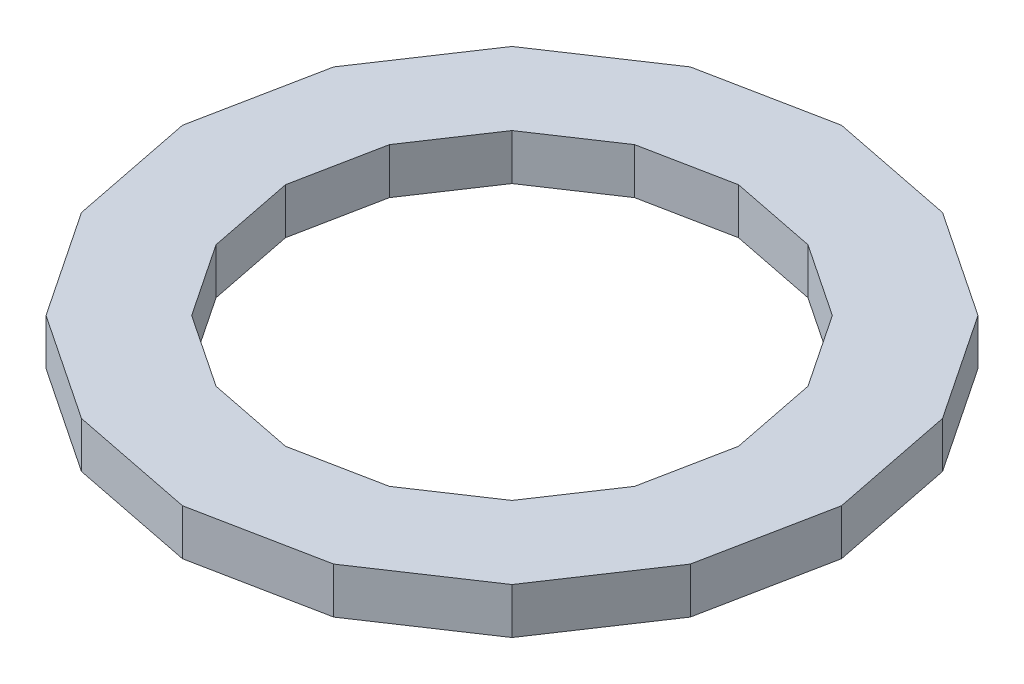
SolidWorks part; units mm, degrees
ref_plane "Front Plane" through (0, 0, 0) normal (0, 0, 1) x (1, 0, 0)
ref_plane "Top Plane" through (0, 0, 0) normal (0, 1, 0) x (1, 0, 0)
ref_plane "Right Plane" through (0, 0, 0) normal (1, 0, 0) x (0, 0, -1)
sketch "Sketch1" plane through (0, 0, 0) normal (0, 1, 0) x (1, 0, 0)
  line L1 (93.9748, 0) -> (86.8214, 35.9626)
  line L2 (86.8214, 35.9626) -> (66.4502, 66.4502)
  line L3 (66.4502, 66.4502) -> (35.9626, 86.8214)
  line L4 (35.9626, 86.8214) -> (0, 93.9748)
  line L5 (0, 93.9748) -> (-35.9626, 86.8214)
  line L6 (-35.9626, 86.8214) -> (-66.4502, 66.4502)
  line L7 (-66.4502, 66.4502) -> (-86.8214, 35.9626)
  line L8 (-86.8214, 35.9626) -> (-93.9748, 0)
  line L9 (-93.9748, 0) -> (-86.8214, -35.9626)
  line L10 (-86.8214, -35.9626) -> (-66.4502, -66.4502)
  line L11 (-66.4502, -66.4502) -> (-35.9626, -86.8214)
  line L12 (-35.9626, -86.8214) -> (0, -93.9748)
  line L13 (0, -93.9748) -> (35.9626, -86.8214)
  line L14 (35.9626, -86.8214) -> (66.4502, -66.4502)
  line L15 (66.4502, -66.4502) -> (86.8214, -35.9626)
  line L16 (86.8214, -35.9626) -> (93.9748, 0)
  line L17 (136.7059, 0) -> (126.2998, 52.3151)
  line L18 (126.2998, 52.3151) -> (96.6657, 96.6657)
  line L19 (96.6657, 96.6657) -> (52.3151, 126.2998)
  line L20 (52.3151, 126.2998) -> (0, 136.7059)
  line L21 (0, 136.7059) -> (-52.3151, 126.2998)
  line L22 (-52.3151, 126.2998) -> (-96.6657, 96.6657)
  line L23 (-96.6657, 96.6657) -> (-126.2998, 52.3151)
  line L24 (-126.2998, 52.3151) -> (-136.7059, 0)
  line L25 (-136.7059, 0) -> (-126.2998, -52.3151)
  line L26 (-126.2998, -52.3151) -> (-96.6657, -96.6657)
  line L27 (-96.6657, -96.6657) -> (-52.3151, -126.2998)
  line L28 (-52.3151, -126.2998) -> (0, -136.7059)
  line L29 (0, -136.7059) -> (52.3151, -126.2998)
  line L30 (52.3151, -126.2998) -> (96.6657, -96.6657)
  line L31 (96.6657, -96.6657) -> (126.2998, -52.3151)
  line L32 (126.2998, -52.3151) -> (136.7059, 0)
  circle A0 centre (0, 0) radius 92.1691 construction
  circle A1 centre (0, 0) radius 134.0791 construction
  dimension "D1" = 41.91
  dimension "D2" = 53.34
extrude "Boss-Extrude1" add sketch "Sketch1" along normal blind 19.05
